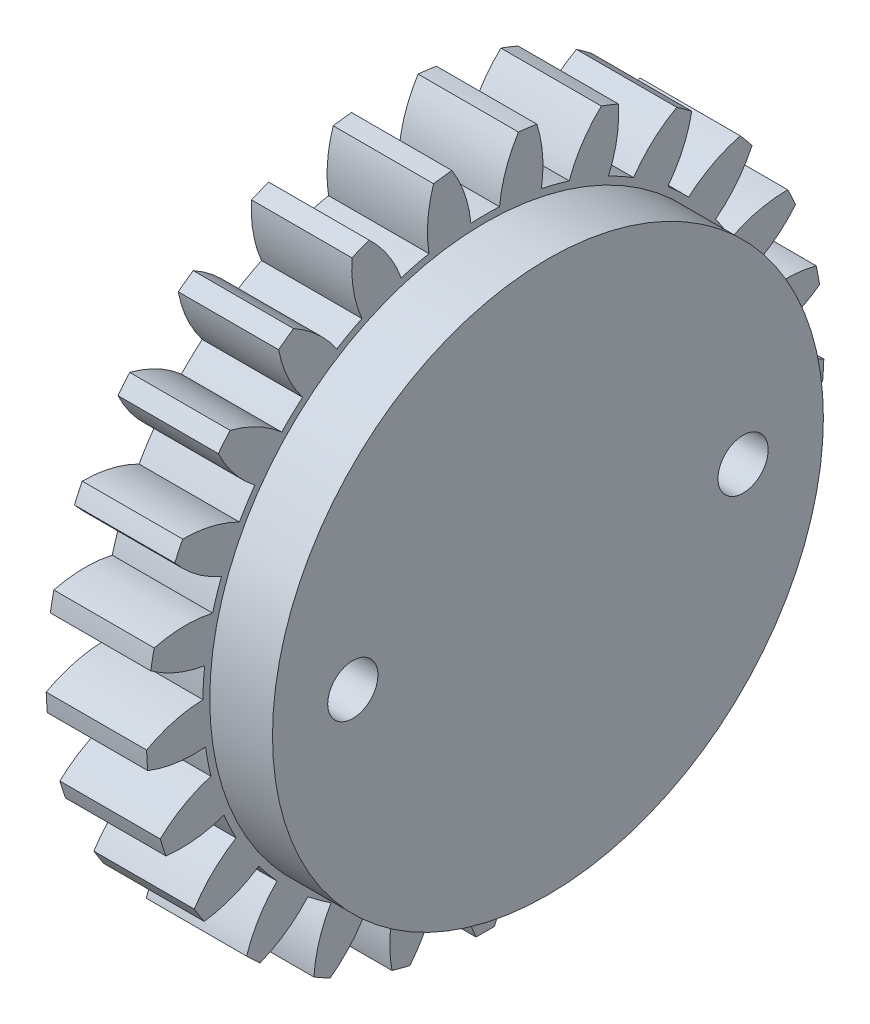
SolidWorks part; units mm, degrees
ref_plane "Plane1" through (0, 0, 0) normal (0, 0, 1) x (1, 0, 0)
ref_plane "Plane2" through (0, 0, 0) normal (0, 1, 0) x (1, 0, 0)
ref_plane "Plane3" through (0, 0, 0) normal (1, 0, 0) x (0, 0, -1)
sketch "HoldingSke" plane through (0, 0, 0) normal (0, 1, 0) x (1, 0, 0)
  line L0 (0, 0) -> (0.9063, -0.4226)
  line L1 (-15, 0) -> (100, 0) construction
  line L2 (0, 0) -> (-2.1039, 2.3779)
  line L3 (0, 0) -> (-11.863, 4.5341)
  line L4 (0, 0) -> (7.8269, 3.6497)
  line L5 (0, 0) -> (-46.8476, -17.4728)
  line L6 (0, 0) -> (-3.3159, -2.2372)
  line L7 (-2.1039, 2.3779) -> (8.6586, 51.2059)
  line L8 (-76.2, 54.61) -> (-75.7, 54.61)
  line L9 (-67.7845, 28.3722) -> (-49.3413, 33.142)
  line L10 (-76.2, 71.12) -> (104.1128, 71.12)
  line L11 (0, 0) -> (-4, 0)
  line L12 (-76.2, 101.6) -> (-76.162, 101.6)
  line L13 (24.9733, 27.94) -> (52.9518, 28.4284)
  line L14 (24.9733, 27.94) -> (24.9743, 27.94)
  line L15 (24.9733, 27.94) -> (100.4006, 29.5858)
  line L16 (-63.627, -1) -> (-12.827, -1)
  circle A0 centre (0, 0) radius 1.5
  circle A1 centre (0, 0) radius 11.249
  circle A2 centre (0, 0) radius 37.5
  circle A3 centre (0, 0) radius 1.5
  dimension "MHD" = 22.498
  dimension "Hub_dia" = 75
  dimension "Bore" = 3
  dimension "MBD" = 3
  dimension "Num_teeth" = 25
  dimension "Pitch" = 1
  dimension "Overall_len" = 50
  dimension "Show_teeth" = 25
  dimension "Thickness" = 4
  dimension "OAL" = 50.0001
  dimension "T_dim" = 0.5
  dimension "Ap" = 14.5
  dimension "H" = 19.05
  dimension "Pitch_radius" = 180.3128
  dimension "Width" = 4
  dimension "Backlash" = 0.038
  dimension "Addendum_fac" = 1
  dimension "Dedendum_fac" = 1.25
  dimension "Clearance_fac" = 0.25
  dimension "Dedendum_add" = 0.001
  dimension "Module" = 1
sketch "BasProSke" plane through (0, 0, 0) normal (0, 1, 0) x (1, 0, 0)
  line L0 (-10, 0) -> (60, 0) construction
  line L1 (0, 0) -> (0, 13.5)
  line L2 (0, 0) -> (4, 0)
  line L3 (4, 0) -> (4, 13.5)
  line L4 (4, 13.5) -> (0, 13.5)
  dimension "Thickness" = 4
  dimension "Diameter" = 27
revolve "Base-Revolve" add sketch "BasProSke" angle 360 about L0
sketch "TooCutSke" plane through (0, 0, 0) normal (1, 0, 0) x (0, 0, -1)
  line L1 (0, 0) -> (0, 107) construction
  line L2 (0, 0) -> (-0.8514, 12.471) construction
  line L3 (0, 0) -> (-3.1282, 24.7619) construction
  line L4 (-0.8514, 12.471) -> (-1.5641, 12.3809) construction
  arc A0 (0.5708, 11.2345) -> (-0.5708, 11.2345) centre (0, 0) ccw
  arc A1 (1.3416, 13.4587) -> (-1.3416, 13.4587) centre (0, 0) ccw
  circle A2 centre (0, 0) radius 12.5 construction
  circle A3 centre (0, 0) radius 12.1018 construction
  arc A4 (-0.5708, 11.2345) -> (-1.3416, 13.4587) centre (-5.5478, 10.7553) ccw
  arc A5 (1.3416, 13.4587) -> (0.5708, 11.2345) centre (5.5478, 10.7553) ccw
  dimension "Root_dia" = 22.498
  dimension "Overcut_dia" = 27.0508
  dimension "Pitch_dia" = 25
  dimension "Base_dia" = 24.2037
  dimension "Flank_rad" = 5
  dimension "Half_ang" = 7.2
  dimension "Half_CT" = 0.7184
extrude "ToothCut" cut sketch "TooCutSke" along normal through all
fillet "Breaks" [suppressed] radius 0.02
fillet "RootFillets" [suppressed] radius 0.251
pattern_circular "TeethCuts" count 25 every 14.4 about axis through (-10, 0, 0) along (1, 0, 0) of "ToothCut", "RootFillets", "Breaks"
sketch "HubNeaOneSke" plane through (0, 0, 0) normal (-1, 0, 0) x (0, 0, 1)
  circle A0 centre (0, 0) radius 11.249
  dimension "Diameter" = 22.498
extrude "HubNearOne" [suppressed] add sketch "HubNeaOneSke" along normal blind 46.0001
sketch "HubNeaBotSke" plane through (0, 0, 0) normal (-1, 0, 0) x (0, 0, 1)
  circle A0 centre (0, 0) radius 11.249
  dimension "Diameter" = 22.498
extrude "HubNearBoth" [suppressed] add sketch "HubNeaBotSke" along normal blind 23
ref_plane "FarPln" through (4, 0, 0) normal (1, 0, 0) x (0, 0, -1)
sketch "HubFarSke" plane through (4, 0, 0) normal (1, 0, 0) x (0, 0, -1)
  circle A0 centre (0, 0) radius 11.249
  dimension "Diameter" = 22.498
extrude "HubFar" [suppressed] add sketch "HubFarSke" along normal blind 23
sketch "BorSke" plane through (0, 0, 0) normal (1, 0, 0) x (0, 0, -1)
  circle A0 centre (0, 0) radius 1.5
  dimension "Diameter" = 3
extrude "Bore" cut sketch "BorSke" along normal mid plane 100.0001
sketch "KeySke" plane through (0, 0, 0) normal (1, 0, 0) x (0, 0, -1)
  line L0 (-0.6, 0) -> (-0.6, 2)
  line L1 (-0.6, 2) -> (0.6, 2)
  line L2 (0.6, 2) -> (0.6, 0)
  line L3 (0, 0) -> (0, 34) construction
  line L4 (-0.6, 0) -> (0.6, 0)
  dimension "Offset" = 2
  dimension "Width" = 1.2
extrude "Keyway" [suppressed] cut sketch "KeySke" along normal mid plane 100.0001
pattern_circular "Keyway2" [suppressed] count 2 every 90 about axis through (-10, 0, 0) along (1, 0, 0)
sketch "Esquisse1" plane through (4, 0, 0) normal (1, 0, 0) x (0, 0, -1)
  circle A0 centre (0, 0) radius 4.0151
extrude "Boss.-Extru.1" add sketch "Esquisse1" against normal up to surface (4 mm away) up to face at (0, 0, -1.5)
sketch "Esquisse3" plane through (4, 0, 0) normal (1, 0, 0) x (0, 0, -1)
  circle A0 centre (0, 0) radius 10.975
  dimension "D1" = 21.95
extrude "Boss.-Extru.2" add sketch "Esquisse3" along normal blind 2.5
sketch "Esquisse2" plane through (4, 0, 0) normal (1, 0, 0) x (0, 0, -1)
  line L0 (-7.775, 0) -> (7.775, 0) construction
  circle A0 centre (-7.775, 0) radius 1
  circle A1 centre (7.775, 0) radius 1
  point P4 (0, 0)
  point P7 (0, 0)
  point P8 (0, 0)
  dimension "D1" = 2
  dimension "D2" = 2
  dimension "D3" = 15.55
extrude "Enlèv. mat.-Extru.1" cut sketch "Esquisse2" along normal through all both and the other way through all
sketch "Esquisse4" plane through (0, 0, 0) normal (-1, 0, 0) x (0, 0, 1)
  circle A0 centre (-7.775, 0) radius 2
  circle A1 centre (7.775, 0) radius 2
  dimension "D1" = 4
  dimension "4" = 4
extrude "Enlèv. mat.-Extru.2" cut sketch "Esquisse4" against normal blind 2.5
equation "' \"Module@HoldingSke\" = 6.35"
equation "' \"Num_teeth@HoldingSke\" = 12"
equation "' \"Ap@HoldingSke\" =  20"
equation "' \"Ap@HoldingSke\" = 20"
equation "' \"Width@HoldingSke\" = 0.5 * 25.4"
equation "' \"Hub_dia@HoldingSke\"= 1 * 25.4"
equation "' \"Hub_dia@HoldingSke\" = 1 * 25.4"
equation "' \"Overall_len@HoldingSke\" = 1.0 * 25.4"
equation "' \"Bore@HoldingSke\" = 0.75 * 25.4"
equation "' \"T_dim@HoldingSke\" = 0.1 * 25.4"
equation "' \"Width@KeySke\" = 0.25 * 25.4"
equation "' \"Show_teeth@HoldingSke\" = 13"
equation "' \"Backlash@HoldingSke\" = 0.009 * 25.4"
equation "' \"Addendum_fac@HoldingSke\" = 1.0"
equation "' \"Dedendum_fac@HoldingSke\" = 1.25"
equation "' \"Dedendum_add@HoldingSke\" = 0.00005 * 25.4"
equation "' \"Clearance_fac@HoldingSke\" = 0.25"
equation "\"Pitch@HoldingSke\" = 1 / \"Module@HoldingSke\""
equation "\"Overcut_dia@TooCutSke\" = (\"Num_teeth@HoldingSke\" + 2 * \"Addendum_fac@HoldingSke\") / \"Pitch@HoldingSke\" + 0.002 * 25.4"
equation "\"Pitch_dia@TooCutSke\" = \"Num_teeth@HoldingSke\" / \"Pitch@HoldingSke\""
equation "\"Base_dia@TooCutSke\" = \"Num_teeth@HoldingSke\" / \"Pitch@HoldingSke\" * cos((\"Ap@HoldingSke\"  * 3.14159265 / 180))"
equation "\"Root_dia@TooCutSke\" = (\"Num_teeth@HoldingSke\" + 2) / \"Pitch@HoldingSke\" - 2 * (\"Addendum_fac@HoldingSke\" + \"Dedendum_fac@HoldingSke\") / \"Pitch@HoldingSke\" - \"Dedendum_add@HoldingSke\" * 2"
equation "\"Half_ang@TooCutSke\" = 180 / \"Num_teeth@HoldingSke\""
equation "\"Half_CT@TooCutSke\" = \"Num_teeth@HoldingSke\" / \"Pitch@HoldingSke\" * sin((3.14159265 / 2 / \"Num_teeth@HoldingSke\")) / 2 - 7 * \"Backlash@HoldingSke\" / 4"
equation "\"Flank_rad@TooCutSke\" = \"Num_teeth@HoldingSke\" / \"Pitch@HoldingSke\" / 5"
equation "\"Radius@RootFillets\" = \"Clearance_fac@HoldingSke\" / \"Pitch@HoldingSke\" + \"Dedendum_add@HoldingSke\""
equation "\"Break_rad@Breaks\" = 0.02 / \"Pitch@HoldingSke\""
equation "\"Thickness@HoldingSke\" = \"Width@HoldingSke\""
equation "\"OAL@HoldingSke\" = \"Thickness@HoldingSke\""
equation "\"MHD@HoldingSke\" = (\"Num_teeth@HoldingSke\" + 2) / \"Pitch@HoldingSke\" - 2 * (\"Addendum_fac@HoldingSke\" + \"Dedendum_fac@HoldingSke\")  / \"Pitch@HoldingSke\" - \"Dedendum_add@HoldingSke\" * 2"
equation "\"MBD@HoldingSke\" = (\"Num_teeth@HoldingSke\" + 2) / \"Pitch@HoldingSke\" - 2 * (\"Addendum_fac@HoldingSke\" + \"Dedendum_fac@HoldingSke\")  / \"Pitch@HoldingSke\" - \"Dedendum_add@HoldingSke\" * 2 - 0.002 * 25.4"
equation "\"MHD@HoldingSke\" = ((sgn( \"MHD@HoldingSke\" - \"Hub_dia@HoldingSke\" )-1)*( \"MHD@HoldingSke\" - \"Hub_dia@HoldingSke\" ))/-2+ \"Hub_dia@HoldingSke\""
equation "\"MBD@HoldingSke\" = ((sgn( \"MBD@HoldingSke\" - \"Bore@HoldingSke\" )-1)*( \"MBD@HoldingSke\" - \"Bore@HoldingSke\" ))/-2+ \"Bore@HoldingSke\""
equation "\"OAL@HoldingSke\" = ((sgn( \"OAL@HoldingSke\" - \"Overall_len@HoldingSke\" )+1)*( \"OAL@HoldingSke\" - \"Overall_len@HoldingSke\" ))/2 + \"Overall_len@HoldingSke\" + 0.000002 * 25.4"
equation "\"Num_teeth@TeethCuts\" = int( \"Show_teeth@HoldingSke\" ) + 1"
equation "\"Num_teeth@TeethCuts\" = ((sgn( \"Num_teeth@TeethCuts\" - \"Num_teeth@HoldingSke\" )-1)*( \"Num_teeth@TeethCuts\" - \"Num_teeth@HoldingSke\" ))/-2+ \"Num_teeth@HoldingSke\""
equation "\"Num_teeth@TeethCuts\" = ((sgn( \"Num_teeth@TeethCuts\" - 2.0)+1)*( \"Num_teeth@TeethCuts\" - 2.0))/2 +2.0"
equation "\"Angle@TeethCuts\" = 360.0 / \"Num_teeth@HoldingSke\""
equation "\"Diameter@BasProSke\" = (\"Num_teeth@HoldingSke\" + 2 * \"Addendum_fac@HoldingSke\") / \"Pitch@HoldingSke\""
equation "\"Thickness@BasProSke\"  = \"Thickness@HoldingSke\""
equation "' \"Fillet_rad@BasProSke\" =  \"Thickness@HoldingSke\" * 0.05"
equation "' \"Fillet_rad@BasProSke\" = \"Thickness@HoldingSke\" * 0.05"
equation "\"MHD@HoldingSke\" = ((sgn( \"MHD@HoldingSke\" - \"Root_dia@TooCutSke\" )-1)*( \"MHD@HoldingSke\" - \"Root_dia@TooCutSke\" ))/-2+ \"Root_dia@TooCutSke\""
equation "\"Diameter@HubNeaOneSke\" = \"MHD@HoldingSke\""
equation "\"Length@HubNearOne\" = \"OAL@HoldingSke\" - \"Thickness@BasProSke\""
equation "\"Diameter@HubNeaBotSke\" = \"MHD@HoldingSke\""
equation "\"Length@HubNearBoth\" = ( \"OAL@HoldingSke\" - \"Thickness@BasProSke\" ) / 2.0"
equation "\"Thickness@FarPln\" = \"Thickness@BasProSke\""
equation "\"Diameter@HubFarSke\" = \"MHD@HoldingSke\""
equation "\"Length@HubFar\" = ( \"OAL@HoldingSke\" - \"Thickness@BasProSke\" ) / 2.0"
equation "\"Diameter@BorSke\" = \"MBD@HoldingSke\""
equation "\"D1@Bore\" = \"OAL@HoldingSke\" * 2.0"
equation "\"D1@Keyway\" = \"OAL@HoldingSke\" * 2.0"
equation "\"Offset@KeySke\" = \"T_dim@HoldingSke\" + \"MBD@HoldingSke\" / 2.0"
